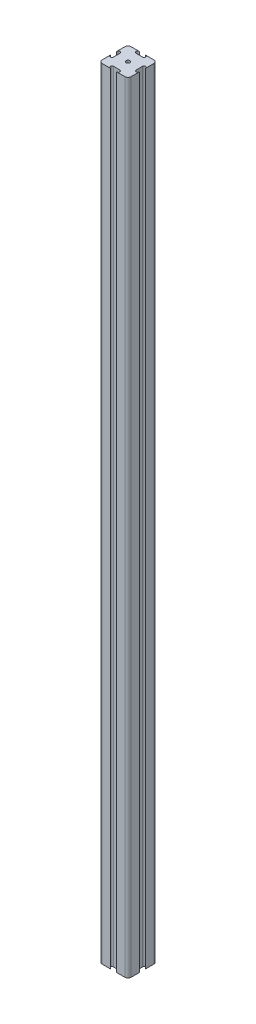
SolidWorks part; units mm, degrees
ref_plane "Front Plane" through (0, 0, 0) normal (0, 0, 1) x (1, 0, 0)
ref_plane "Top Plane" through (0, 0, 0) normal (0, 1, 0) x (1, 0, 0)
ref_plane "Right Plane" through (0, 0, 0) normal (1, 0, 0) x (0, 0, -1)
sketch "Esquisse4" plane through (0, 0, 0) normal (0, 1, 0) x (1, 0, 0)
  line L0 (-17.5, 22.5) -> (-5, 22.5)
  line L1 (22.5, 5) -> (22.5, 17.5)
  line L2 (0, 0) -> (22.5, 0) construction
  line L3 (5, 22.5) -> (17.5, 22.5)
  line L4 (0, 22.5) -> (0, 0) construction
  line L5 (-5, -17.5) -> (5, -17.5)
  line L6 (5, -22.5) -> (17.5, -22.5)
  line L7 (17.5, 5) -> (17.5, -5)
  line L8 (-5, -22.5) -> (-17.5, -22.5)
  line L10 (-5, 20) -> (5, 20) construction
  line L11 (0, 0) -> (0, -28.4326) construction
  line L12 (-5, 17.5) -> (5, 17.5)
  line L13 (17.5, 22.5) -> (17.5, -22.5) construction
  line L14 (-22.5, 17.5) -> (-22.5, 5)
  line L15 (-22.5, -5) -> (-22.5, -17.5)
  line L17 (-17.5, 5) -> (-17.5, -5)
  line L18 (0, 0) -> (-28.2169, 0) construction
  line L19 (22.5, -5) -> (22.5, -17.5)
  arc A0 (17.5, 22.5) -> (22.5, 17.5) centre (17.5, 17.5) cw
  arc A1 (17.5, -22.5) -> (22.5, -17.5) centre (17.5, -17.5) ccw
  arc A2 (-22.5, -17.5) -> (-17.5, -22.5) centre (-17.5, -17.5) ccw
  arc A3 (-17.5, 22.5) -> (-22.5, 17.5) centre (-17.5, 17.5) ccw
  arc A5 (-5, 22.5) -> (-5, 17.5) centre (-5, 20) ccw
  arc A6 (5, 17.5) -> (5, 22.5) centre (5, 20) ccw
  arc A7 (-5, -17.5) -> (-5, -22.5) centre (-5, -20) ccw
  arc A8 (5, -22.5) -> (5, -17.5) centre (5, -20) ccw
  arc A9 (-17.5, -5) -> (-22.5, -5) centre (-20, -5) cw
  arc A10 (22.5, -5) -> (17.5, -5) centre (20, -5) cw
  arc A11 (-17.5, 5) -> (-22.5, 5) centre (-20, 5) ccw
  arc A12 (22.5, 5) -> (17.5, 5) centre (20, 5) ccw
  point P8 (22.5, 22.5)
  point P13 (0, -17.5)
  point P20 (-22.5, 22.5)
  point P23 (0, 20)
  dimension "D4" = 5
  dimension "D6" = 5
  dimension "D7" = 5
  dimension "D8" = 5
  dimension "D20" = 10
  dimension "D24" = 12.5
  dimension "D2" = 22.5
  dimension "D3" = 45
  dimension "D5" = 10
  dimension "D10" = 10
  dimension "D11" = 12.5
  dimension "D12" = 22.5
  dimension "D13" = 5
  dimension "D14" = 17.5
  dimension "D15" = 12.5
  dimension "D16" = 45
  dimension "D17" = 2.5
  dimension "D18" = 5
  dimension "D19" = 45
  dimension "D21" = 5
  dimension "D22" = 17.5
  dimension "D23" = 10
  dimension "D25" = 5
extrude "Boss.-Extru.2" add sketch "Esquisse4" along normal blind 1210 contours L15 A2 L8 A7 L5 A8 L6 A1 L19 A10 L7 A12 L1 A0 L3 A6 L12 A5 L0 A3 L14 A11 L17 A9
sketch "Esquisse5" plane through (0, 0, 0) normal (0, -1, 0) x (1, 0, 0)
  circle A0 centre (0, 0) radius 3
extrude "Enlèv. mat.-Extru.1" cut sketch "Esquisse5" against normal through all
